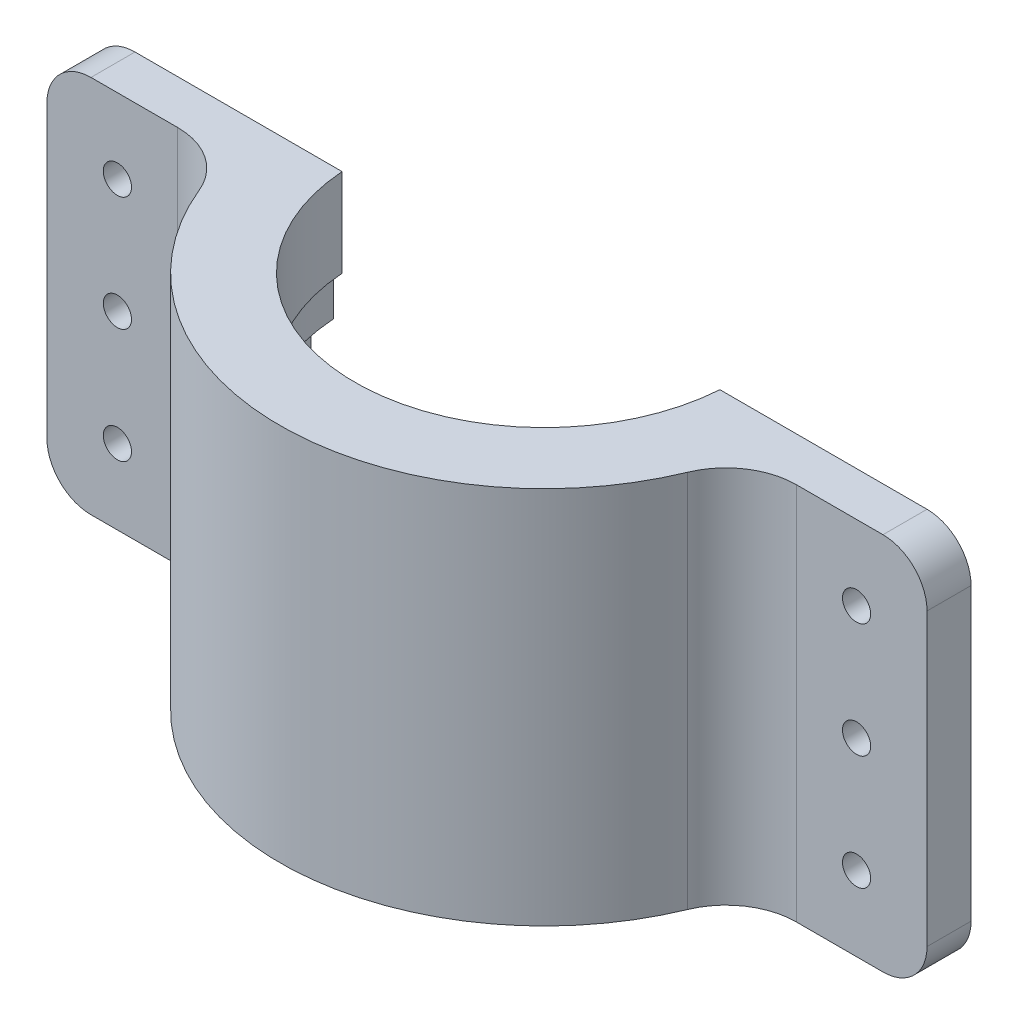
SolidWorks part; units mm, degrees
ref_plane "前视基准面" through (0, 0, 0) normal (0, 0, 1) x (1, 0, 0)
ref_plane "上视基准面" through (0, 0, 0) normal (0, 1, 0) x (1, 0, 0)
ref_plane "右视基准面" through (0, 0, 0) normal (1, 0, 0) x (0, 0, -1)
other "Configuration Table"
sketch "草图1" plane through (0, 0, 0) normal (0, 0, 1) x (1, 0, 0)
  line L0 (0, 80.8793) -> (0, -79.9315) construction
  line L1 (22.5, 29.4673) -> (21.5, 29.4673)
  line L2 (21.5, 29.4673) -> (21.5, 39.4673)
  line L3 (22.5, 29.4673) -> (22.5, 24.4673)
  line L4 (22.5, 24.4673) -> (25, 24.4673)
  line L5 (25, 24.4673) -> (25, 19.4673)
  line L6 (25, 19.4673) -> (22.5, 19.4673)
  line L7 (22.5, 19.4673) -> (22.5, 14.4673)
  line L8 (22.5, 14.4673) -> (25, 14.4673)
  line L9 (25, 14.4673) -> (25, 9.4673)
  line L10 (25, 9.4673) -> (22.5, 9.4673)
  line L11 (22.5, 9.4673) -> (22.5, 4.4673)
  line L12 (22.5, 4.4673) -> (21.5, 4.4673)
  line L13 (21.5, 4.4673) -> (21.5, -3.5327)
  line L14 (21.5, -3.5327) -> (30, -3.5327)
  line L15 (30, -3.5327) -> (30, 39.4673)
  line L16 (21.5, 39.4673) -> (30, 39.4673)
  point P3 (25, 11.9673)
  point P20 (20, 29.4673)
  dimension "D1" = 50
  dimension "D2" = 2.5
  dimension "D3" = 2.5
  dimension "D4" = 2.5
  dimension "D5" = 2.5
  dimension "D6" = 1
  dimension "D7" = 1
  dimension "D8" = 5
  dimension "D9" = 5
  dimension "D10" = 5
  dimension "D11" = 5
  dimension "D12" = 5
  dimension "D13" = 5
  dimension "D14" = 8
  dimension "D15" = 10
revolve "旋转1" add sketch "草图1" angle 180 about L0
sketch "草图2" plane through (0, 0, 0) normal (0, 0, -1) x (-1, 0, 0)
  line L1 (-40.19, 52.2425) -> (42.4144, 52.2425)
  line L2 (-40.19, 52.2425) -> (-40.19, -17.1169)
  line L3 (-40.19, -17.1169) -> (42.4144, -17.1169)
  line L4 (42.4144, 52.2425) -> (42.4144, -17.1169)
extrude "切除-拉伸1" cut sketch "草图2" against normal blind 1.5
sketch "草图3" plane through (0, 0, 1.5) normal (0, 0, -1) x (-1, 0, 0)
  line L0 (0, 55.8217) -> (0, -26.8029) construction
  line L1 (-29.9625, 39.4673) -> (-44.9625, 39.4673)
  line L2 (-49.9625, 34.4673) -> (-49.9625, 1.4673)
  line L5 (-44.9625, -3.5327) -> (-29.9625, -3.5327)
  line L10 (-29.9625, 39.4673) -> (-26.9625, 39.4673)
  line L11 (-21.4476, 39.4673) -> (-29.9625, 39.4673) construction
  line L12 (-26.9625, 39.4673) -> (-26.9625, -3.5327)
  line L13 (-29.9625, -3.5327) -> (-21.4476, -3.5327) construction
  line L14 (-26.9625, -3.5327) -> (-29.9625, -3.5327)
  line L15 (26.9625, -3.5327) -> (29.9625, -3.5327)
  line L16 (26.9625, 39.4673) -> (26.9625, -3.5327)
  line L17 (29.9625, 39.4673) -> (26.9625, 39.4673)
  line L18 (44.9625, -3.5327) -> (29.9625, -3.5327)
  line L19 (49.9625, 34.4673) -> (49.9625, 1.4673)
  line L20 (29.9625, 39.4673) -> (44.9625, 39.4673)
  circle A0 centre (-41.9625, 30.9673) radius 1.6
  circle A1 centre (-41.9625, 17.9673) radius 1.6
  circle A2 centre (-41.9625, 4.9673) radius 1.6
  arc A3 (-49.9625, 1.4673) -> (-44.9625, -3.5327) centre (-44.9625, 1.4673) ccw
  arc A4 (-44.9625, 39.4673) -> (-49.9625, 34.4673) centre (-44.9625, 34.4673) ccw
  arc A10 (44.9625, 39.4673) -> (49.9625, 34.4673) centre (44.9625, 34.4673) cw
  arc A11 (49.9625, 1.4673) -> (44.9625, -3.5327) centre (44.9625, 1.4673) cw
  circle A12 centre (41.9625, 4.9673) radius 1.6
  circle A13 centre (41.9625, 17.9673) radius 1.6
  circle A14 centre (41.9625, 30.9673) radius 1.6
  point P25 (-49.9625, 39.4673)
  point P42 (49.9625, 39.4673)
  line M14 (21.4476, -3.5327) -> (29.9625, -3.5327)
  line M15 (29.9625, -3.5327) -> (29.9625, 39.4673)
  line M16 (29.9625, 39.4673) -> (21.4476, 39.4673)
  dimension "D2" = 3.2
  dimension "D3" = 3.2
  dimension "D4" = 3.2
  dimension "D7" = 5
  dimension "D1" = 20
  dimension "D5" = 13
  dimension "D6" = 13
  dimension "D8" = 3
  dimension "D9" = 21.5
  dimension "D10" = 15
extrude "凸台-拉伸1" add sketch "草图3" against normal blind 5 contours A11 L19 A10 L20 L18 A13 A12 A14 M15 | L16 M16 M14 M15 | L1 A4 L2 A3 L5 L14 L12 L10 A0 A1 A2
fillet "圆角1" radius 8 2 edges at (-29.2874, 17.9673, 6.5) (29.2874, 17.9673, 6.5)
